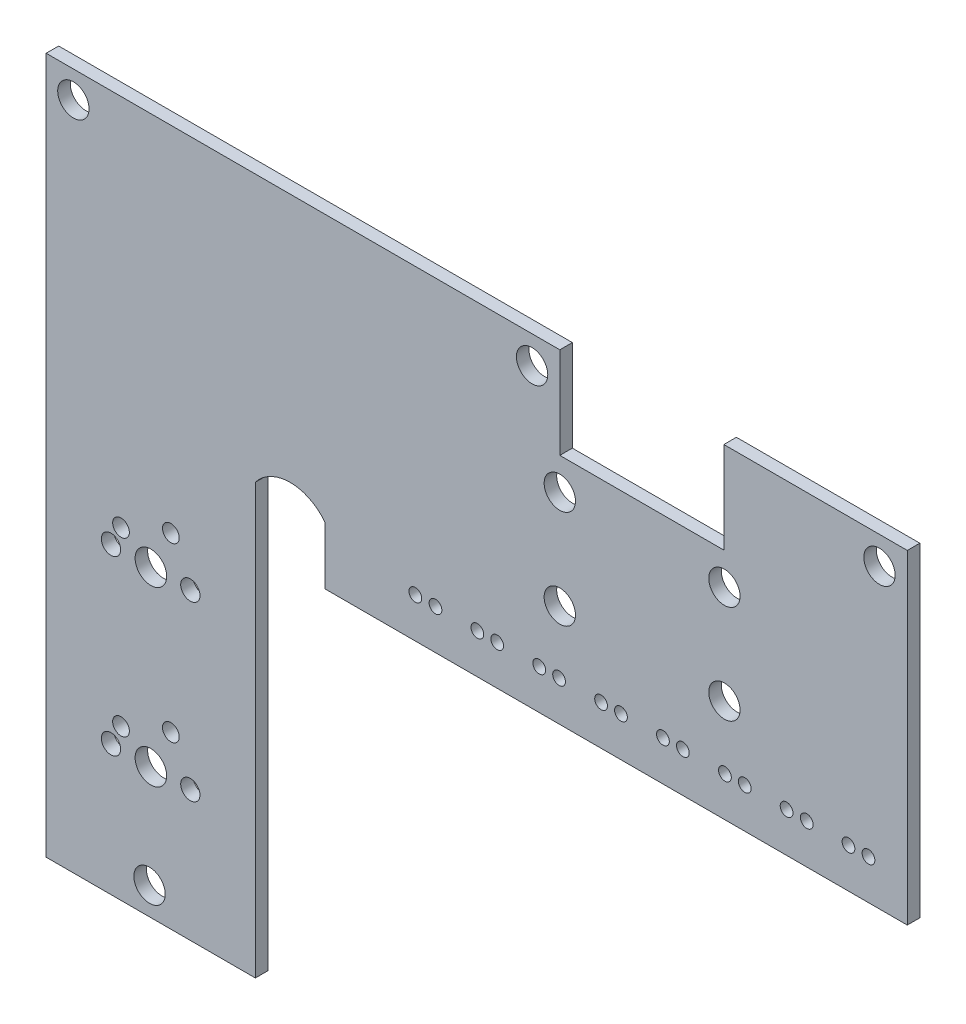
SolidWorks part; units mm, degrees
ref_plane "Front Plane" through (0, 0, 0) normal (0, 0, 1) x (1, 0, 0)
ref_plane "Top Plane" through (0, 0, 0) normal (0, 1, 0) x (1, 0, 0)
ref_plane "Right Plane" through (0, 0, 0) normal (1, 0, 0) x (0, 0, -1)
sketch "Sketch1" plane through (0, 0, 0) normal (0, 0, 1) x (1, 0, 0)
  line L0 (0.4032, 89.1745) -> (104.5432, 89.1745) construction
  line L7 (-43.4054, 89.1029) -> (66.4496, 89.1029) construction
  line L8 (-43.391, 0.2893) -> (-43.391, 89.1047)
  line L9 (-43.391, 89.1047) -> (22.13, 89.1047)
  line L10 (22.13, 89.1047) -> (22.13, 77.4402)
  line L11 (22.13, 77.4402) -> (43.0551, 77.4402)
  line L12 (43.0551, 77.4402) -> (43.0551, 89.1047)
  line L13 (43.0551, 89.1047) -> (66.4542, 89.1047)
  line L14 (66.4542, 89.1047) -> (66.4542, 48.4765)
  line L17 (-43.391, 0.2893) -> (-16.7059, 0.2893)
  line L22 (66.4542, 48.4765) -> (66.4542, 47.7145)
  line L23 (66.4542, 47.7145) -> (-7.8159, 47.7145)
  line L25 (-16.7059, 0.2893) -> (-16.7059, 55.0603)
  line L26 (-7.8159, 47.7145) -> (-7.8159, 55.0603)
  circle A0 centre (-39.9195, 85.6855) radius 2
  circle A3 centre (62.9044, 85.5773) radius 2
  circle A4 centre (18.5938, 85.5773) radius 2
  circle A5 centre (22.13, 73.3705) radius 2
  circle A6 centre (43.1257, 73.3705) radius 2
  circle A7 centre (-30.2049, 3.786) radius 2
  circle A8 centre (3.702, 52.8154) radius 0.8135
  circle A9 centre (6.2701, 52.8154) radius 0.8135
  circle A10 centre (11.6119, 52.7938) radius 0.8135
  circle A11 centre (14.1442, 52.7938) radius 0.8135
  circle A12 centre (19.5022, 52.7938) radius 0.8135
  circle A13 centre (22.0368, 52.7938) radius 0.8135
  circle A14 centre (27.3924, 52.7938) radius 0.8135
  circle A15 centre (29.9317, 52.7938) radius 0.8135
  circle A16 centre (35.2828, 52.8282) radius 0.8135
  circle A17 centre (37.8281, 52.8282) radius 0.8135
  circle A18 centre (43.1904, 52.7938) radius 0.8135
  circle A19 centre (45.7204, 52.8282) radius 0.8135
  circle A20 centre (51.0557, 52.7938) radius 0.8135
  circle A21 centre (53.6305, 52.7938) radius 0.8135
  circle A22 centre (58.9499, 52.7938) radius 0.8135
  circle A23 centre (61.5012, 52.7938) radius 0.8135
  circle A24 centre (-35.1209, 38.9976) radius 1.2305
  circle A26 centre (-33.8447, 41.4782) radius 1.0656
  circle A28 centre (-25.0025, 38.9976) radius 1.2305
  circle A30 centre (-27.4864, 44.0455) radius 1.0656
  circle A31 centre (-35.1209, 16.9596) radius 1.2305
  circle A32 centre (-33.8447, 19.5257) radius 1.0656
  circle A34 centre (-25.0025, 16.9596) radius 1.2305
  circle A35 centre (-27.4864, 22.0582) radius 1.0656
  circle A36 centre (22.13, 60.7975) radius 2
  circle A37 centre (43.1257, 60.7975) radius 2
  circle A38 centre (-30.0359, 38.9976) radius 2.0132
  circle A39 centre (-30.0359, 38.9976) radius 2.0132
  circle A40 centre (-30.0359, 16.9596) radius 2.0132
  arc A42 (-7.8159, 55.0603) -> (-16.7059, 55.0603) centre (-12.2609, 51.6739) ccw
  point P82 (-11.9015, 49.729)
  dimension "D2" = 109.855
  dimension "D1" = 0.762
extrude "Boss-Extrude1" add sketch "Sketch1" along normal blind 1.6
sketch "Sketch2" plane through (0, 0, 0) normal (0, 0, 1) x (1, 0, 0)
  line L0 (16.9717, 1120.6131) -> (77.0525, 1120.6131) construction
  line L1 (-43.3843, 89.0419) -> (66.4707, 89.0419) construction
  dimension "D1" = 109.855
sketch "Sketch6" plane through (0, 0, 1.6) normal (0, 0, 1) x (1, 0, 0)
  line L0 (-43.323, 89.1318) -> (66.532, 89.1318) construction
  dimension "D1" = 109.855
